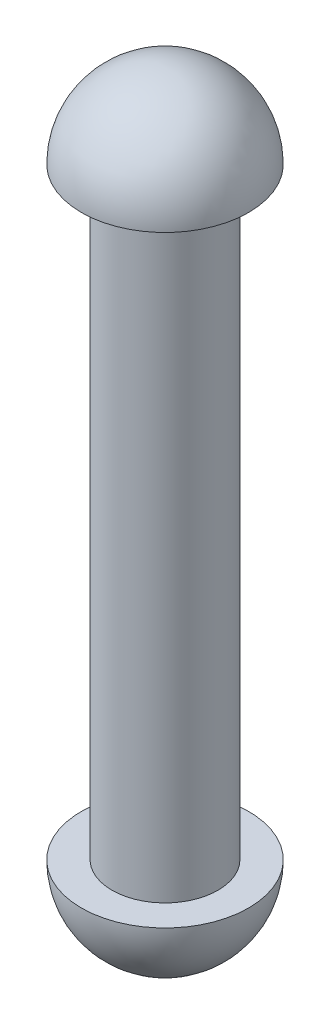
SolidWorks part; units mm, degrees
ref_plane "Front Plane" through (0, 0, 0) normal (0, 0, 1) x (1, 0, 0)
ref_plane "Top Plane" through (0, 0, 0) normal (0, 1, 0) x (1, 0, 0)
ref_plane "Right Plane" through (0, 0, 0) normal (1, 0, 0) x (0, 0, -1)
sketch "Sketch1" plane through (0, 0, 0) normal (0, 0, 1) x (1, 0, 0)
  line L0 (-30, 0) -> (-19, 0)
  line L1 (-19, 0) -> (-19, -216)
  line L2 (0, 0) -> (0, 30)
  line L3 (0, 0) -> (0, -216)
  line L4 (0, -216) -> (0, 0)
  line L6 (0, -216) -> (0, -246)
  line L7 (-30, -216) -> (-19, -216)
  arc A0 (0, 30) -> (-30, 0) centre (0, 0) ccw
  arc A1 (0, -246) -> (-30, -216) centre (0, -216) cw
  dimension "D1" = 60
  dimension "D3" = 19
revolve "Revolve1" add sketch "Sketch1" angle 360 about L3
